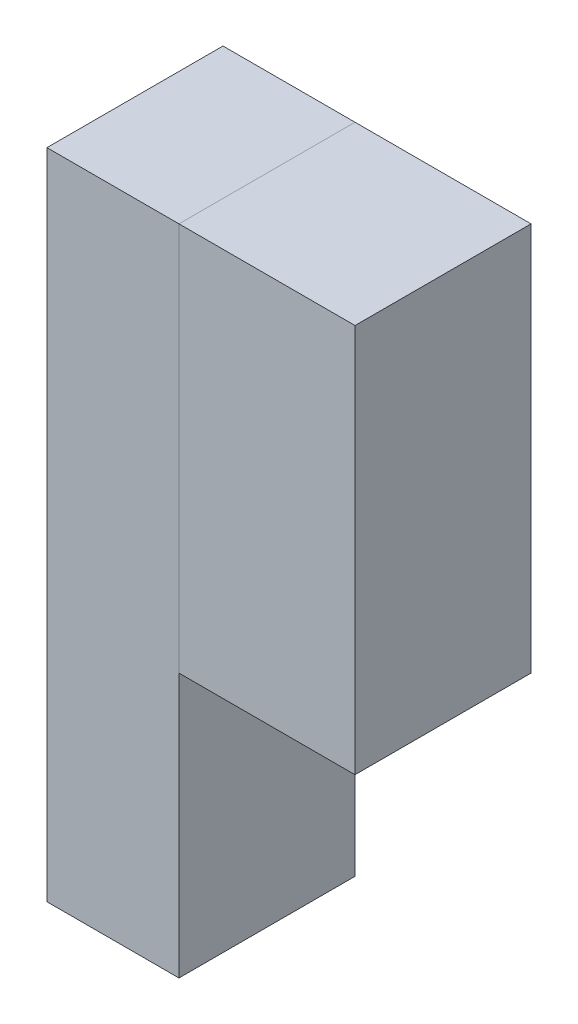
SolidWorks part; units mm, degrees
ref_plane "Спереди" through (0, 0, 0) normal (0, 0, 1) x (1, 0, 0)
ref_plane "Сверху" through (0, 0, 0) normal (0, 1, 0) x (1, 0, 0)
ref_plane "Справа" through (0, 0, 0) normal (1, 0, 0) x (0, 0, -1)
other "Configuration Table"
sketch "Эскиз1" plane through (0, 0, 0) normal (0, 1, 0) x (1, 0, 0)
  line L1 (0, 0) -> (450, 0)
  line L2 (0, 0) -> (0, 600)
  line L3 (0, 600) -> (450, 600)
  line L4 (450, 0) -> (450, 600)
  dimension "D1" = 450
  dimension "D2" = 600
extrude "Бобышка-Вытянуть1" add sketch "Эскиз1" along normal blind 2226
sketch "Эскиз2" plane through (450, 0, 0) normal (1, 0, 0) x (0, 0, -1)
  line L0 (600, 2226) -> (600, 0) construction
  line L1 (0, 2226) -> (600, 2226)
  line L2 (0, 2226) -> (0, 900)
  line L3 (0, 900) -> (600, 900)
  line L4 (600, 2226) -> (600, 900)
  line L5 (0, 0) -> (600, 0) construction
  dimension "D1" = 900
extrude "Бобышка-Вытянуть2" add sketch "Эскиз2" along normal blind 600 separate body
